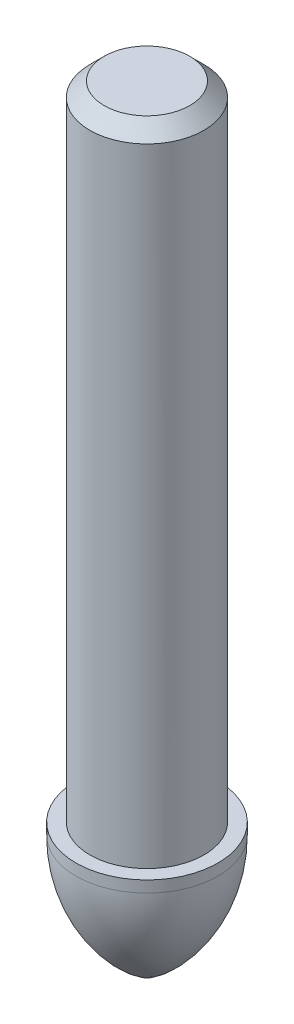
SolidWorks part; units mm, degrees
material "1.2316 (X36CrMo17)"
ref_plane "Front Plane" through (0, 0, 0) normal (0, 0, 1) x (1, 0, 0)
ref_plane "Top Plane" through (0, 0, 0) normal (0, 1, 0) x (1, 0, 0)
ref_plane "Right Plane" through (0, 0, 0) normal (1, 0, 0) x (0, 0, -1)
sketch "Sketch1" plane through (0, 0, 0) normal (0, 0, 1) x (1, 0, 0)
  line L0 (0, 0) -> (0, -59.4187) construction
  line L1 (0, 0) -> (4, 0)
  line L2 (4, 0) -> (4, -45)
  line L3 (4, -45) -> (4.976, -45)
  line L4 (4.976, -45) -> (4.976, -45.8)
  line L5 (4.976, -45.8) -> (-4.976, -45.8) construction
  line L6 (0, -54.1889) -> (0, 0)
  arc A1 (0.7148, -53.9644) -> (4.976, -45.8) centre (-4.976, -45.8) ccw
  arc A2 (0, -54.1889) -> (0.7148, -53.9644) centre (0, -52.9389) ccw
  arc A3 (0, -51.6889) -> (0, -54.1889) centre (0, -52.9389) ccw construction
  arc A4 (0.7148, -53.9644) -> (0, -51.6889) centre (0, -52.9389) ccw construction
  arc A5 (0, -54.4187) -> (0.7148, -53.9644) centre (-4.976, -45.8) ccw construction
  dimension "D6" = 2.5
  dimension "D1" = 9.952
  dimension "PilotDiameter" = 9.952
  dimension "D2" = 8
  dimension "D4" = 9.952
  dimension "ShankLength" = 45.8
  dimension "D3" = 0.8
  dimension "D5" = 5
revolve "Revolve1" add sketch "Sketch1" angle 360 about L0
chamfer "Chamfer1" distance 1 angle 45 1 edges at (-4, 0, 0)
cosmetic thread "Cosmetic Thread2" parameters "D1"=16, "D2"=6.619
equation "\"D4@Sketch1\" = \"PilotDiameter@Sketch1\""
equation "\"Pierce Punch Diameter\"= 10"
equation "\"PilotDiameter@Sketch1\"= \"Pierce Punch Diameter\" - 0.03 * 1.6"
equation "\"Material Thickness\"= 1.6mm"
equation "\"Punch Height\"= 41mm"
equation "\"ShankLength@Sketch1\"= \"Punch Height\" + \"Thread into Punch Holder\" + \"Pilot Engagement Length\" - 6"
equation "\"Thread into Punch Holder\"= 10mm"
equation "\"Pilot Engagement Length\"= \"Material Thickness\" * 0.5"
